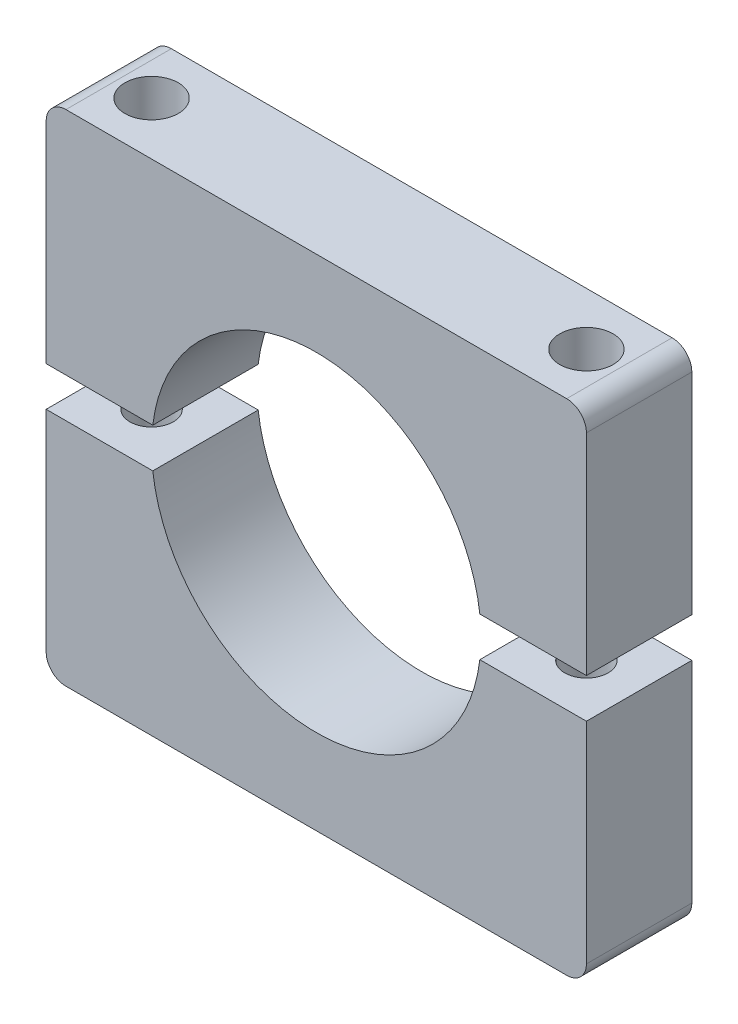
SolidWorks part; units mm, degrees
material "6061 合金"
ref_plane "前视基准面" through (0, 0, 0) normal (0, 0, 1) x (1, 0, 0)
ref_plane "上视基准面" through (0, 0, 0) normal (0, 1, 0) x (1, 0, 0)
ref_plane "右视基准面" through (0, 0, 0) normal (1, 0, 0) x (0, 0, -1)
other "Configuration Table"
sketch "草图1" plane through (0, 0, 0) normal (0, 0, 1) x (1, 0, 0)
  line L1 (-20.5, -18.95) -> (20.5, -18.95)
  line L2 (-20.5, -18.95) -> (-20.5, 18.95)
  line L3 (-20.5, 18.95) -> (20.5, 18.95)
  line L4 (20.5, -18.95) -> (20.5, 18.95)
  line L5 (-20.5, -18.95) -> (20.5, 18.95) construction
  line L6 (-20.5, 18.95) -> (20.5, -18.95) construction
  circle A0 centre (0, 0) radius 12.5
  point P0 (0, 0)
  dimension "D2" = 25
  dimension "D3" = 8
  dimension "D1" = 37.9
extrude "凸台-拉伸1" add sketch "草图1" along normal mid plane 8 from offset 0
fillet "圆角1" radius 1.5 4 edges at (20.5, -18.95, 0) (-20.5, -18.95, 0) (-20.5, 18.95, 0) (20.5, 18.95, 0)
sketch "草图2" plane through (0, 0, 4) normal (0, 0, 1) x (1, 0, 0)
  line L1 (-25, -1.5) -> (25, -1.5)
  line L2 (-25, -1.5) -> (-25, 1.5)
  line L3 (-25, 1.5) -> (25, 1.5)
  line L4 (25, -1.5) -> (25, 1.5)
  line L5 (-25, -1.5) -> (25, 1.5) construction
  line L6 (-25, 1.5) -> (25, -1.5) construction
  point P0 (0, 0)
  dimension "D1" = 3
  dimension "D2" = 50
extrude "切除-拉伸1" cut sketch "草图2" against normal mid plane 38
sketch "草图3" plane through (0, 18.95, 0) normal (0, 1, 0) x (1, 0, 0)
  line L0 (-16.5, 0) -> (16.5, 0) construction
  line L1 (20.5, 4) -> (20.5, -4) construction
  circle A0 centre (16.5, 0) radius 2.025
  circle A1 centre (-16.5, 0) radius 2.025
  point P4 (0, 0)
  dimension "D2" = 4.05
  dimension "D1" = 4
extrude "切除-拉伸2" cut sketch "草图3" against normal mid plane 38
hole_wizard "M4 螺纹孔1" positions "草图4" profile "草图5" tap size "M4" standard "GB" end condition through all
sketch "草图4" plane through (0, -1.5, 0) normal (0, 1, 0) x (1, 0, 0)
  point P0 (-16.5, 0)
  point P3 (16.5, 0)
sketch "草图5" plane through (-16.5, -1.5, 0) normal (1, 0, 0) x (0, 0, 1)
  line L0 (0, 0) -> (0, 17.45)
  line L1 (0, 17.45) -> (1.65, 17.45)
  line L2 (1.65, 17.45) -> (1.65, 0)
  line L5 (1.65, 0) -> (0, 0)
  line L11 (0, -6.35) -> (0, 107.95) construction
  dimension "通孔螺纹孔钻头直径" = 3.3
  dimension "通孔螺纹孔钻头深度" = 17.45
cosmetic thread "孔螺蚊线1" parameters "D2"=4
cosmetic thread "孔螺蚊线2" parameters "D2"=4
